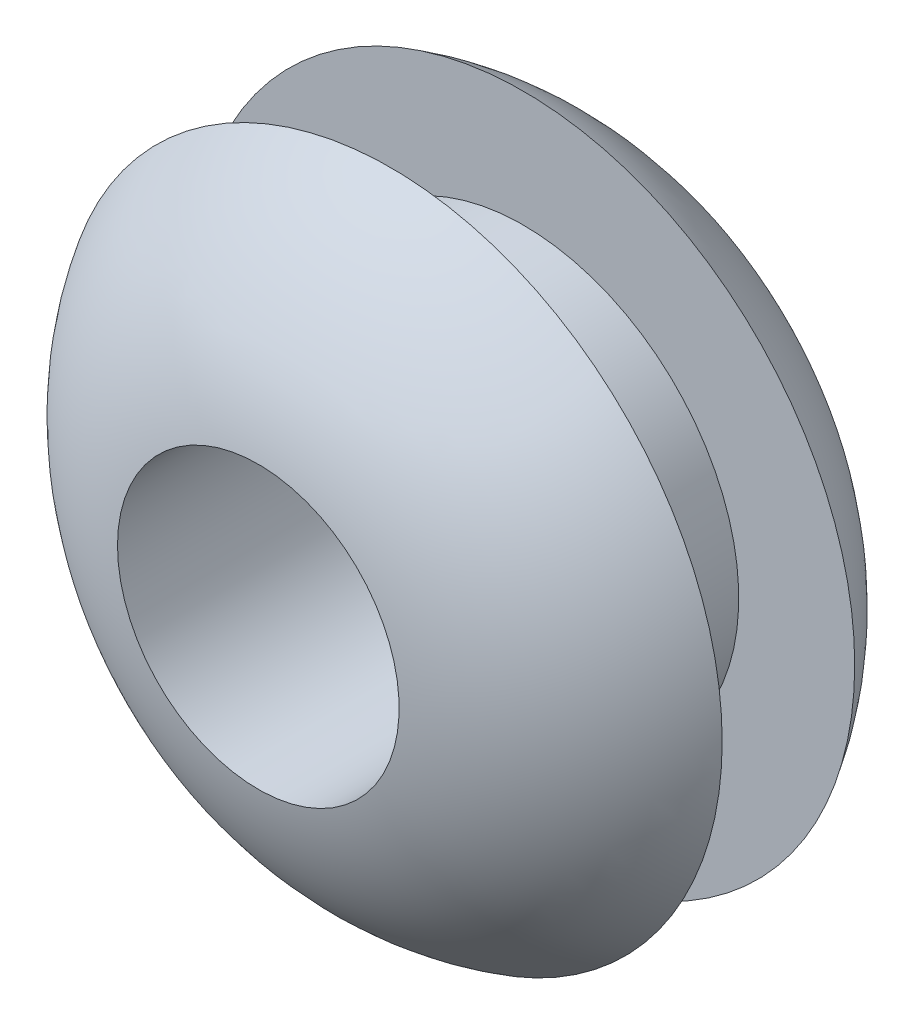
SolidWorks part; units mm, degrees
material "Резина"
ref_plane "Спереди" through (0, 0, 0) normal (0, 0, 1) x (1, 0, 0)
ref_plane "Сверху" through (0, 0, 0) normal (0, 1, 0) x (1, 0, 0)
ref_plane "Справа" through (0, 0, 0) normal (1, 0, 0) x (0, 0, -1)
sketch "Эскиз1" plane through (0, 0, 0) normal (1, 0, 0) x (0, 0, -1)
  line L0 (0, 0) -> (-18.1831, 0) construction
  line L1 (-4.3291, 3.3734) -> (-13.8541, 3.3734)
  line L2 (-9.0916, 0) -> (-9.0916, 10.3187) construction
  line L3 (-10.6791, 5.1594) -> (-7.5041, 5.1594)
  line L4 (-7.5041, 5.1594) -> (-7.5041, 7.9375)
  line L5 (-10.6791, 5.1594) -> (-10.6791, 7.9375)
  arc A0 (-4.3291, 3.3734) -> (-7.5041, 7.9375) centre (-10.8809, 2.202) ccw
  arc A1 (-13.8541, 3.3734) -> (-10.6791, 7.9375) centre (-7.3022, 2.202) cw
  point P8 (-9.0916, 3.3734)
  point P16 (-9.0916, 5.1594)
  dimension "D6" = 10.3187
  dimension "D1" = 6.7469
  dimension "D2" = 9.525
  dimension "D3" = 15.875
  dimension "D4" = 3.175
revolve "Повернуть1" add sketch "Эскиз1" angle 360 about L0
